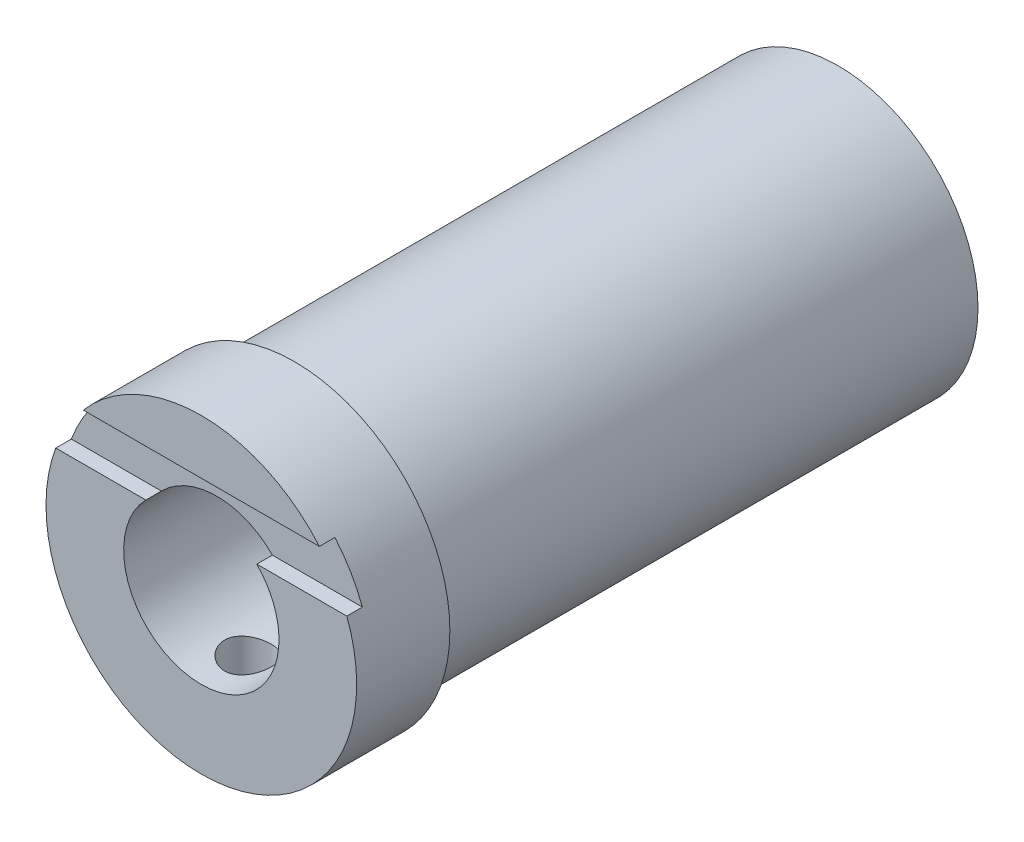
SolidWorks part; units mm, degrees
ref_plane "Спереди" through (0, 0, 0) normal (0, 0, 1) x (1, 0, 0)
ref_plane "Сверху" through (0, 0, 0) normal (0, 1, 0) x (1, 0, 0)
ref_plane "Справа" through (0, 0, 0) normal (1, 0, 0) x (0, 0, -1)
sketch "Эскиз1" plane through (0, 0, 0) normal (0, 0, 1) x (1, 0, 0)
  circle A0 centre (0, 0) radius 9
  circle A1 centre (0, 0) radius 5
extrude "Бобышка-Вытянуть1" add sketch "Эскиз1" along normal blind 35
sketch "Эскиз2" plane through (0, 0, 35) normal (0, 0, 1) x (1, 0, 0)
  circle A0 centre (0, 0) radius 5
  circle A1 centre (0, 0) radius 10
extrude "Бобышка-Вытянуть2" add sketch "Эскиз2" along normal blind 6
sketch "Эскиз3" plane through (0, 0, 41) normal (0, 0, 1) x (1, 0, 0)
  line L1 (-11.475, 6.499) -> (11.6703, 6.499)
  line L2 (-11.475, 6.499) -> (-11.475, 3.499)
  line L3 (-11.475, 3.499) -> (11.6703, 3.499)
  line L4 (11.6703, 6.499) -> (11.6703, 3.499)
  line L5 (-11.475, 6.499) -> (11.6703, 3.499) construction
  line L6 (-11.475, 3.499) -> (11.6703, 6.499) construction
  circle A0 centre (0, 0) radius 5 construction
  point P0 (0.0977, 4.999)
  dimension "D1" = 3
extrude "Вырез-Вытянуть1" cut sketch "Эскиз3" against normal blind 1
sketch "Эскиз4" plane through (0, 0, 0) normal (0, 1, 0) x (1, 0, 0)
  circle A0 centre (0, -38) radius 1.5
extrude "Вырез-Вытянуть2" cut sketch "Эскиз4" against normal up to next
